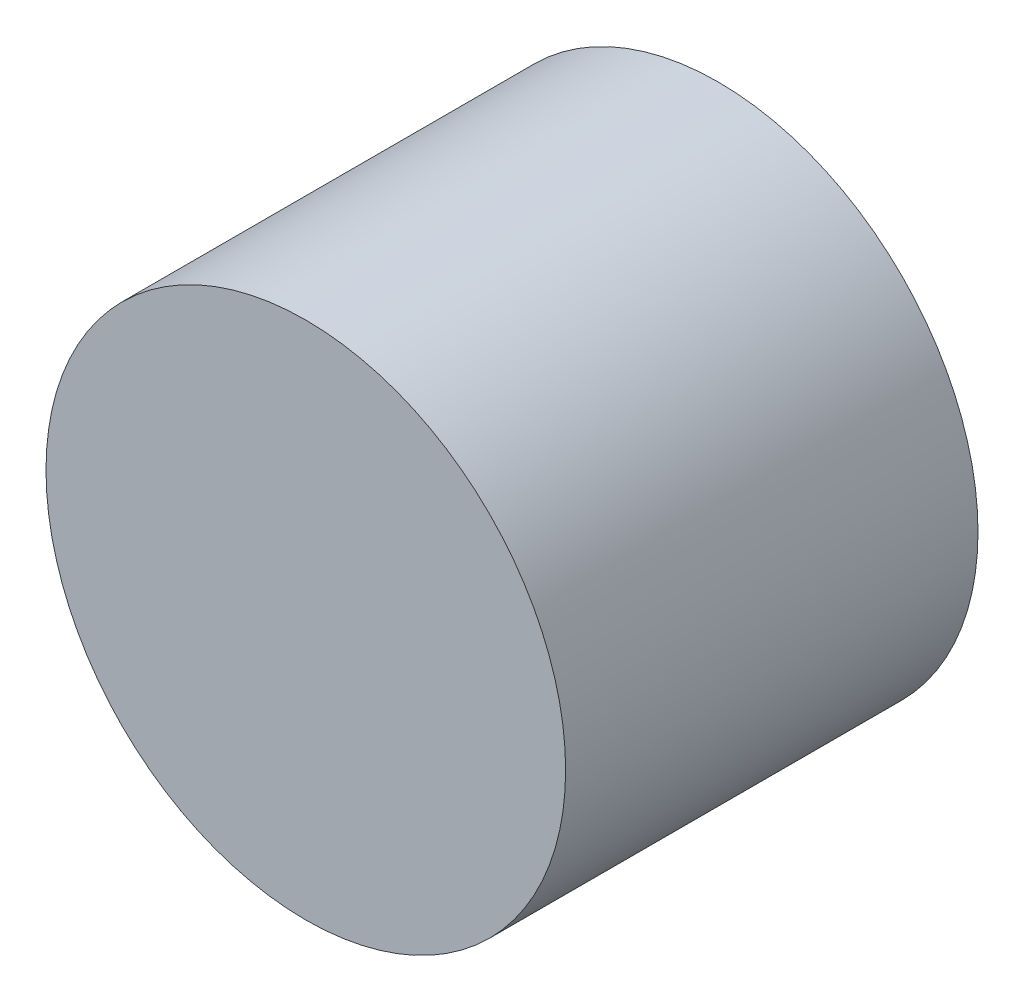
SolidWorks part; units mm, degrees
ref_plane "Front Plane" through (0, 0, 0) normal (0, 0, 1) x (1, 0, 0)
ref_plane "Top Plane" through (0, 0, 0) normal (0, 1, 0) x (1, 0, 0)
ref_plane "Right Plane" through (0, 0, 0) normal (1, 0, 0) x (0, 0, -1)
sketch "CurveSketch" plane through (0, 0, 0) normal (0, 0, 1) x (1, 0, 0)
  circle A0 centre (-3.719, 5.173) radius 7.391
  dimension "D1" = 7.391
extrude "CurveBoss" add sketch "CurveSketch" along normal blind 11.731
